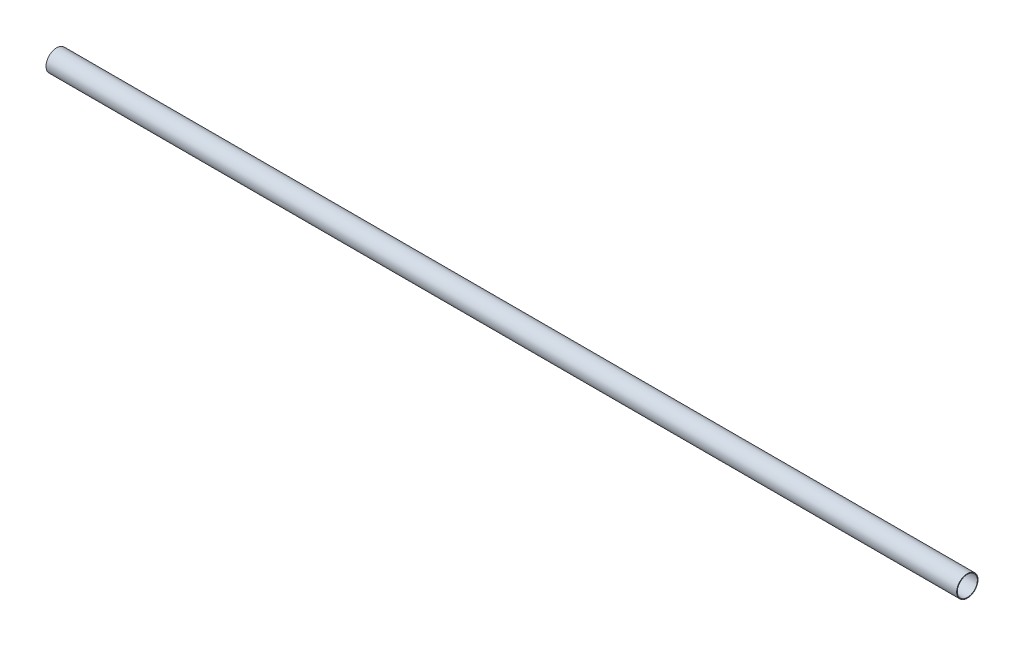
SolidWorks part; units mm, degrees
material "Copper"
ref_plane "Front" through (0, 0, 0) normal (0, 0, 1) x (1, 0, 0)
ref_plane "Top" through (0, 0, 0) normal (0, 1, 0) x (1, 0, 0)
ref_plane "Right" through (0, 0, 0) normal (1, 0, 0) x (0, 0, -1)
sketch "Sketch1" plane through (0, 0, 0) normal (1, 0, 0) x (0, 0, -1)
  circle A0 centre (0, 0) radius 14.2875
  circle A1 centre (0, 0) radius 13.3985
  point P4 (14.2875, 0)
  point P5 (13.3985, 0)
  dimension "OD" = 28.575
  dimension "ID" = 26.797
  dimension "Wall" = 0.889
extrude "Extrude1" add sketch "Sketch1" along normal mid plane 1219.2
sketch "Sketch2" plane through (0, 0, 0) normal (0, 0, 1) x (1, 0, 0)
  line L0 (-609.6, 0) -> (609.6, 0) construction
  line L1 (-609.6, 14.2875) -> (-609.6, -14.2875) construction
